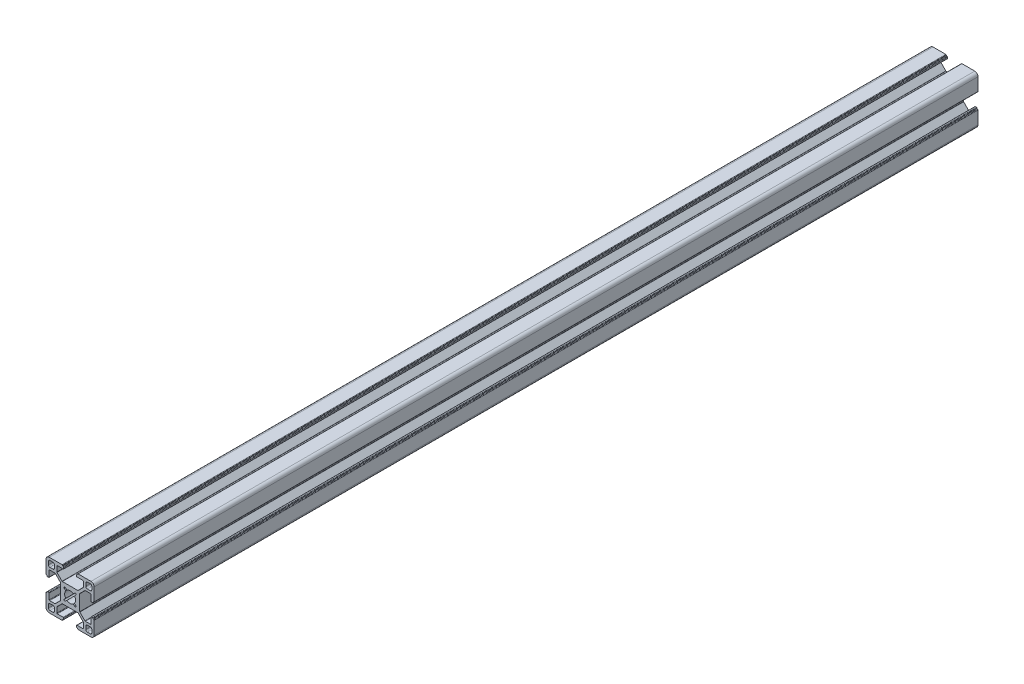
SolidWorks part; units mm, degrees
ref_plane "Piano frontale" through (0, 0, 0) normal (0, 0, 1) x (1, 0, 0)
ref_plane "Piano superiore" through (0, 0, 0) normal (0, 1, 0) x (1, 0, 0)
ref_plane "Piano destro" through (0, 0, 0) normal (1, 0, 0) x (0, 0, -1)
ref_plane "Piano1" through (0, 0, 25) normal (0, 0, 1) x (1, 0, 0)
sketch "Schizzo1" plane through (0, 0, 25) normal (0, 0, 1) x (1, 0, 0)
  line L0 (-12.5625, -9.75) -> (-10.6875, -9.75)
  line L1 (-9.75, -10.6875) -> (-9.75, -12.5625)
  line L2 (-10.6875, -13.5) -> (-12.5625, -13.5)
  line L3 (-13.5, -12.5625) -> (-13.5, -10.6875)
  line L4 (12.5625, 9.75) -> (10.6875, 9.75)
  line L5 (9.75, 10.6875) -> (9.75, 12.5625)
  line L6 (10.6875, 13.5) -> (12.5625, 13.5)
  line L7 (13.5, 12.5625) -> (13.5, 10.6875)
  line L8 (-4.7, -14.7) -> (-4.7, -14.6)
  line L9 (-4.4, -14.3) -> (-4.3, -14.3)
  line L10 (-4, -14) -> (-4, -13.3)
  line L11 (-4.3, -13) -> (-7.95, -13)
  line L12 (-8.25, -12.7) -> (-8.25, -9.4349)
  line L13 (-8.1621, -9.2228) -> (-5.0272, -6.0879)
  line L14 (-4.8151, -6) -> (4.8151, -6)
  line L15 (5.0272, -6.0879) -> (8.1621, -9.2228)
  line L16 (8.25, -9.4349) -> (8.25, -12.7)
  line L17 (7.95, -13) -> (4.3, -13)
  line L18 (4, -13.3) -> (4, -14)
  line L19 (4.3, -14.3) -> (4.4, -14.3)
  line L20 (4.7, -14.6) -> (4.7, -14.7)
  line L21 (5, -15) -> (13, -15)
  line L22 (15, -13) -> (15, -5)
  line L23 (14.7, -4.7) -> (14.6, -4.7)
  line L24 (14.3, -4.4) -> (14.3, -4.3)
  line L25 (14, -4) -> (13.3, -4)
  line L26 (13, -4.3) -> (13, -7.95)
  line L27 (12.7, -8.25) -> (9.4349, -8.25)
  line L28 (9.2228, -8.1621) -> (6.0879, -5.0272)
  line L29 (6, -4.8151) -> (6, 4.8151)
  line L30 (6.0879, 5.0272) -> (9.2228, 8.1621)
  line L31 (9.4349, 8.25) -> (12.7, 8.25)
  line L32 (13, 7.95) -> (13, 4.3)
  line L33 (13.3, 4) -> (14, 4)
  line L34 (14.3, 4.3) -> (14.3, 4.4)
  line L35 (14.6, 4.7) -> (14.7, 4.7)
  line L36 (15, 5) -> (15, 13)
  line L37 (13, 15) -> (5, 15)
  line L38 (4.7, 14.7) -> (4.7, 14.6)
  line L39 (4.4, 14.3) -> (4.3, 14.3)
  line L40 (4, 14) -> (4, 13.3)
  line L41 (4.3, 13) -> (7.95, 13)
  line L42 (8.25, 12.7) -> (8.25, 9.4349)
  line L43 (8.1621, 9.2228) -> (5.0272, 6.0879)
  line L44 (4.8151, 6) -> (-4.8151, 6)
  line L45 (-5.0272, 6.0879) -> (-8.1621, 9.2228)
  line L46 (-8.25, 9.4349) -> (-8.25, 12.7)
  line L47 (-7.95, 13) -> (-4.3, 13)
  line L48 (-4, 13.3) -> (-4, 14)
  line L49 (-4.3, 14.3) -> (-4.4, 14.3)
  line L50 (-4.7, 14.6) -> (-4.7, 14.7)
  line L51 (-5, 15) -> (-13, 15)
  line L52 (-15, 13) -> (-15, 5)
  line L53 (-14.7, 4.7) -> (-14.6, 4.7)
  line L54 (-14.3, 4.4) -> (-14.3, 4.3)
  line L55 (-14, 4) -> (-13.3, 4)
  line L56 (-13, 4.3) -> (-13, 7.95)
  line L57 (-12.7, 8.25) -> (-9.4349, 8.25)
  line L58 (-9.2228, 8.1621) -> (-6.0879, 5.0272)
  line L59 (-6, 4.8151) -> (-6, -4.8151)
  line L60 (-6.0879, -5.0272) -> (-9.2228, -8.1621)
  line L61 (-9.4349, -8.25) -> (-12.7, -8.25)
  line L62 (-13, -7.95) -> (-13, -4.3)
  line L63 (-13.3, -4) -> (-14, -4)
  line L64 (-14.3, -4.3) -> (-14.3, -4.4)
  line L65 (-14.6, -4.7) -> (-14.7, -4.7)
  line L66 (-15, -5) -> (-15, -13)
  line L67 (-13, -15) -> (-5, -15)
  line L68 (2.0101, 2.7422) -> (2.8679, 3.6)
  line L69 (3.6, 2.8679) -> (2.7422, 2.0101)
  line L70 (2.7422, -2.0101) -> (3.6, -2.8679)
  line L71 (2.8679, -3.6) -> (2.0101, -2.7422)
  line L72 (-2.0101, -2.7422) -> (-2.8679, -3.6)
  line L73 (-3.6, -2.8679) -> (-2.7422, -2.0101)
  line L74 (-2.7422, 2.0101) -> (-3.6, 2.8679)
  line L75 (-2.8679, 3.6) -> (-2.0101, 2.7422)
  line L76 (-9.75, 12.5625) -> (-9.75, 10.6875)
  line L77 (-10.6875, 9.75) -> (-12.5625, 9.75)
  line L78 (-13.5, 10.6875) -> (-13.5, 12.5625)
  line L79 (-12.5625, 13.5) -> (-10.6875, 13.5)
  line L80 (9.75, -12.5625) -> (9.75, -10.6875)
  line L81 (10.6875, -9.75) -> (12.5625, -9.75)
  line L82 (13.5, -10.6875) -> (13.5, -12.5625)
  line L83 (12.5625, -13.5) -> (10.6875, -13.5)
  arc A0 (-10.6875, -9.75) -> (-9.75, -10.6875) centre (-10.6875, -10.6875) cw
  arc A1 (-9.75, -12.5625) -> (-10.6875, -13.5) centre (-10.6875, -12.5625) cw
  arc A2 (-12.5625, -13.5) -> (-13.5, -12.5625) centre (-12.5625, -12.5625) cw
  arc A3 (-13.5, -10.6875) -> (-12.5625, -9.75) centre (-12.5625, -10.6875) cw
  arc A4 (10.6875, 9.75) -> (9.75, 10.6875) centre (10.6875, 10.6875) cw
  arc A5 (9.75, 12.5625) -> (10.6875, 13.5) centre (10.6875, 12.5625) cw
  arc A6 (12.5625, 13.5) -> (13.5, 12.5625) centre (12.5625, 12.5625) cw
  arc A7 (13.5, 10.6875) -> (12.5625, 9.75) centre (12.5625, 10.6875) cw
  arc A8 (-5, -15) -> (-4.7, -14.7) centre (-5, -14.7) ccw
  arc A9 (-4.7, -14.6) -> (-4.4, -14.3) centre (-4.4, -14.6) cw
  arc A10 (-4.3, -14.3) -> (-4, -14) centre (-4.3, -14) ccw
  arc A11 (-4, -13.3) -> (-4.3, -13) centre (-4.3, -13.3) ccw
  arc A12 (-7.95, -13) -> (-8.25, -12.7) centre (-7.95, -12.7) cw
  arc A13 (-8.25, -9.4349) -> (-8.1621, -9.2228) centre (-7.95, -9.4349) cw
  arc A14 (-5.0272, -6.0879) -> (-4.8151, -6) centre (-4.8151, -6.3) cw
  arc A15 (4.8151, -6) -> (5.0272, -6.0879) centre (4.8151, -6.3) cw
  arc A16 (8.1621, -9.2228) -> (8.25, -9.4349) centre (7.95, -9.4349) cw
  arc A17 (8.25, -12.7) -> (7.95, -13) centre (7.95, -12.7) cw
  arc A18 (4.3, -13) -> (4, -13.3) centre (4.3, -13.3) ccw
  arc A19 (4, -14) -> (4.3, -14.3) centre (4.3, -14) ccw
  arc A20 (4.4, -14.3) -> (4.7, -14.6) centre (4.4, -14.6) cw
  arc A21 (4.7, -14.7) -> (5, -15) centre (5, -14.7) ccw
  arc A22 (13, -15) -> (15, -13) centre (13, -13) ccw
  arc A23 (15, -5) -> (14.7, -4.7) centre (14.7, -5) ccw
  arc A24 (14.6, -4.7) -> (14.3, -4.4) centre (14.6, -4.4) cw
  arc A25 (14.3, -4.3) -> (14, -4) centre (14, -4.3) ccw
  arc A26 (13.3, -4) -> (13, -4.3) centre (13.3, -4.3) ccw
  arc A27 (13, -7.95) -> (12.7, -8.25) centre (12.7, -7.95) cw
  arc A28 (9.4349, -8.25) -> (9.2228, -8.1621) centre (9.4349, -7.95) cw
  arc A29 (6.0879, -5.0272) -> (6, -4.8151) centre (6.3, -4.8151) cw
  arc A30 (6, 4.8151) -> (6.0879, 5.0272) centre (6.3, 4.8151) cw
  arc A31 (9.2228, 8.1621) -> (9.4349, 8.25) centre (9.4349, 7.95) cw
  arc A32 (12.7, 8.25) -> (13, 7.95) centre (12.7, 7.95) cw
  arc A33 (13, 4.3) -> (13.3, 4) centre (13.3, 4.3) ccw
  arc A34 (14, 4) -> (14.3, 4.3) centre (14, 4.3) ccw
  arc A35 (14.3, 4.4) -> (14.6, 4.7) centre (14.6, 4.4) cw
  arc A36 (14.7, 4.7) -> (15, 5) centre (14.7, 5) ccw
  arc A37 (15, 13) -> (13, 15) centre (13, 13) ccw
  arc A38 (5, 15) -> (4.7, 14.7) centre (5, 14.7) ccw
  arc A39 (4.7, 14.6) -> (4.4, 14.3) centre (4.4, 14.6) cw
  arc A40 (4.3, 14.3) -> (4, 14) centre (4.3, 14) ccw
  arc A41 (4, 13.3) -> (4.3, 13) centre (4.3, 13.3) ccw
  arc A42 (7.95, 13) -> (8.25, 12.7) centre (7.95, 12.7) cw
  arc A43 (8.25, 9.4349) -> (8.1621, 9.2228) centre (7.95, 9.4349) cw
  arc A44 (5.0272, 6.0879) -> (4.8151, 6) centre (4.8151, 6.3) cw
  arc A45 (-4.8151, 6) -> (-5.0272, 6.0879) centre (-4.8151, 6.3) cw
  arc A46 (-8.1621, 9.2228) -> (-8.25, 9.4349) centre (-7.95, 9.4349) cw
  arc A47 (-8.25, 12.7) -> (-7.95, 13) centre (-7.95, 12.7) cw
  arc A48 (-4.3, 13) -> (-4, 13.3) centre (-4.3, 13.3) ccw
  arc A49 (-4, 14) -> (-4.3, 14.3) centre (-4.3, 14) ccw
  arc A50 (-4.4, 14.3) -> (-4.7, 14.6) centre (-4.4, 14.6) cw
  arc A51 (-4.7, 14.7) -> (-5, 15) centre (-5, 14.7) ccw
  arc A52 (-13, 15) -> (-15, 13) centre (-13, 13) ccw
  arc A53 (-15, 5) -> (-14.7, 4.7) centre (-14.7, 5) ccw
  arc A54 (-14.6, 4.7) -> (-14.3, 4.4) centre (-14.6, 4.4) cw
  arc A55 (-14.3, 4.3) -> (-14, 4) centre (-14, 4.3) ccw
  arc A56 (-13.3, 4) -> (-13, 4.3) centre (-13.3, 4.3) ccw
  arc A57 (-13, 7.95) -> (-12.7, 8.25) centre (-12.7, 7.95) cw
  arc A58 (-9.4349, 8.25) -> (-9.2228, 8.1621) centre (-9.4349, 7.95) cw
  arc A59 (-6.0879, 5.0272) -> (-6, 4.8151) centre (-6.3, 4.8151) cw
  arc A60 (-6, -4.8151) -> (-6.0879, -5.0272) centre (-6.3, -4.8151) cw
  arc A61 (-9.2228, -8.1621) -> (-9.4349, -8.25) centre (-9.4349, -7.95) cw
  arc A62 (-12.7, -8.25) -> (-13, -7.95) centre (-12.7, -7.95) cw
  arc A63 (-13, -4.3) -> (-13.3, -4) centre (-13.3, -4.3) ccw
  arc A64 (-14, -4) -> (-14.3, -4.3) centre (-14, -4.3) ccw
  arc A65 (-14.3, -4.4) -> (-14.6, -4.7) centre (-14.6, -4.4) cw
  arc A66 (-14.7, -4.7) -> (-15, -5) centre (-14.7, -5) ccw
  arc A67 (-15, -13) -> (-13, -15) centre (-13, -13) ccw
  arc A68 (2.8679, 3.6) -> (3.6, 2.8679) centre (3.234, 3.234) cw
  arc A69 (2.7422, 2.0101) -> (2.7422, -2.0101) centre (0, 0) cw
  arc A70 (3.6, -2.8679) -> (2.8679, -3.6) centre (3.234, -3.234) cw
  arc A71 (2.0101, -2.7422) -> (-2.0101, -2.7422) centre (0, 0) cw
  arc A72 (-2.8679, -3.6) -> (-3.6, -2.8679) centre (-3.234, -3.234) cw
  arc A73 (-2.7422, -2.0101) -> (-2.7422, 2.0101) centre (0, 0) cw
  arc A74 (-3.6, 2.8679) -> (-2.8679, 3.6) centre (-3.234, 3.234) cw
  arc A75 (-2.0101, 2.7422) -> (2.0101, 2.7422) centre (0, 0) cw
  arc A76 (-9.75, 10.6875) -> (-10.6875, 9.75) centre (-10.6875, 10.6875) cw
  arc A77 (-12.5625, 9.75) -> (-13.5, 10.6875) centre (-12.5625, 10.6875) cw
  arc A78 (-13.5, 12.5625) -> (-12.5625, 13.5) centre (-12.5625, 12.5625) cw
  arc A79 (-10.6875, 13.5) -> (-9.75, 12.5625) centre (-10.6875, 12.5625) cw
  arc A80 (9.75, -10.6875) -> (10.6875, -9.75) centre (10.6875, -10.6875) cw
  arc A81 (12.5625, -9.75) -> (13.5, -10.6875) centre (12.5625, -10.6875) cw
  arc A82 (13.5, -12.5625) -> (12.5625, -13.5) centre (12.5625, -12.5625) cw
  arc A83 (10.6875, -13.5) -> (9.75, -12.5625) centre (10.6875, -12.5625) cw
extrude "Estrusione-Estrusione1" add sketch "Schizzo1" against normal blind 550
